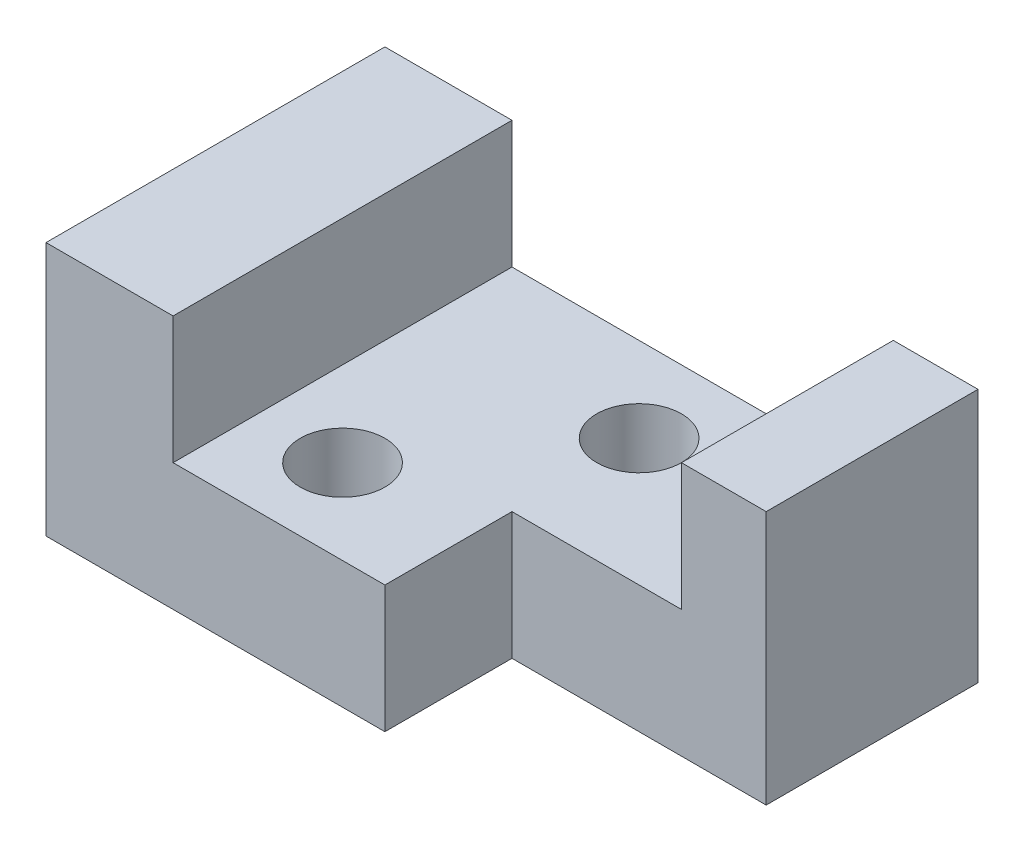
SolidWorks part; units mm, degrees
ref_plane "Front Plane" through (0, 0, 0) normal (0, 0, 1) x (1, 0, 0)
ref_plane "Top Plane" through (0, 0, 0) normal (0, 1, 0) x (1, 0, 0)
ref_plane "Right Plane" through (0, 0, 0) normal (1, 0, 0) x (0, 0, -1)
sketch "Sketch1" plane through (0, 0, 0) normal (0, 0, 1) x (1, 0, 0)
  line L0 (-47.625, 0) -> (41.275, 0)
  line L1 (41.275, 0) -> (41.275, 38.1)
  line L2 (41.275, 38.1) -> (28.575, 38.1)
  line L3 (28.575, 38.1) -> (28.575, 19.05)
  line L4 (28.575, 19.05) -> (-28.575, 19.05)
  line L5 (-28.575, 19.05) -> (-28.575, 38.1)
  line L6 (-28.575, 38.1) -> (-47.625, 38.1)
  line L7 (-47.625, 38.1) -> (-47.625, 0)
  line L8 (55, 0) -> (-55, 0) construction
  line L9 (0, -55) -> (0, 55) construction
  point P10 (0, 19.05)
  dimension "D1" = 88.9
  dimension "D2" = 38.1
  dimension "D3" = 12.7
  dimension "D4" = 19.05
  dimension "D5" = 19.05
  dimension "D6" = 19.05
extrude "Base Feature" add sketch "Sketch1" along normal mid plane 50.8
sketch "Sketch2" plane through (0, 0, 0) normal (0, -1, 0) x (1, 0, 0)
  line L0 (41.275, 25.4) -> (3.175, 25.4)
  line L1 (-47.625, 25.4) -> (41.275, 25.4) construction
  line L2 (3.175, 25.4) -> (3.175, 6.35)
  line L3 (3.175, 6.35) -> (41.275, 6.35)
  line L4 (41.275, 25.4) -> (41.275, -25.4) construction
  line L5 (41.275, 6.35) -> (41.275, 25.4)
  dimension "D1" = 19.05
  dimension "D2" = 38.1
extrude "Altitudual Cut" cut sketch "Sketch2" against normal through all
hole_wizard "1/2 (0.5) Diameter Holes" positions "Hole 1" profile "Hole 2" hole size "1/2" standard "ANSI Inch" end condition through all
sketch "Hole 1" plane through (0, 19.05, 0) normal (0, 1, 0) x (1, 0, 0)
  line L0 (3.175, -25.4) -> (-28.575, -25.4) construction
  line L1 (28.575, 25.4) -> (-28.575, 25.4) construction
  line L2 (3.175, -25.4) -> (3.175, -6.35) construction
  line L3 (28.575, -6.35) -> (28.575, 25.4) construction
  point P0 (-15.875, -12.7)
  point P2 (3.175, 12.7)
  dimension "D1" = 12.7
  dimension "D2" = 12.7
  dimension "D3" = 19.05
  dimension "D4" = 25.4
sketch "Hole 2" plane through (-15.875, 19.05, 12.7) normal (1, 0, 0) x (0, 0, 1)
  line L0 (0, 0) -> (0, 19.05)
  line L1 (0, 19.05) -> (6.35, 19.05)
  line L2 (6.35, 19.05) -> (6.35, 0)
  line L5 (6.35, 0) -> (0, 0)
  line L11 (0, -6.35) -> (0, 107.95) construction
  dimension "Thru Hole Dia." = 12.7
  dimension "Thru Hole Depth" = 19.05
